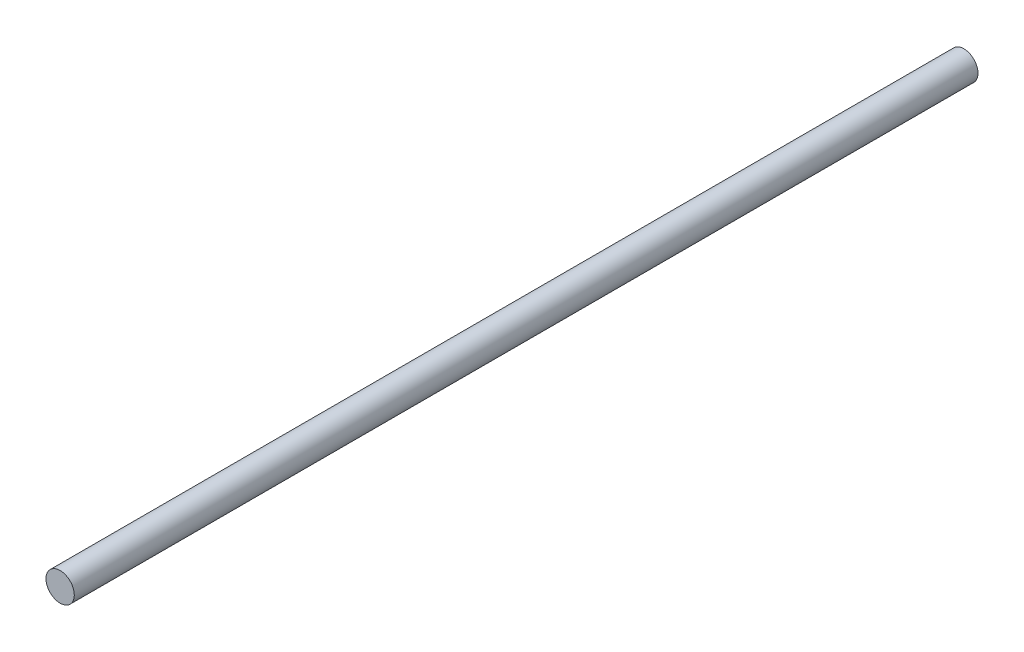
SolidWorks part; units mm, degrees
ref_plane "Front" through (0, 0, 0) normal (0, 0, 1) x (1, 0, 0)
ref_plane "Top" through (0, 0, 0) normal (0, 1, 0) x (1, 0, 0)
ref_plane "Right" through (0, 0, 0) normal (1, 0, 0) x (0, 0, -1)
sketch "Sketch1" plane through (0, 0, 0) normal (0, 0, 1) x (1, 0, 0)
  circle A0 centre (0, 0) radius 4.7
  dimension "D1" = 9.4
extrude "Boss-Extrude1" add sketch "Sketch1" along normal blind 300
